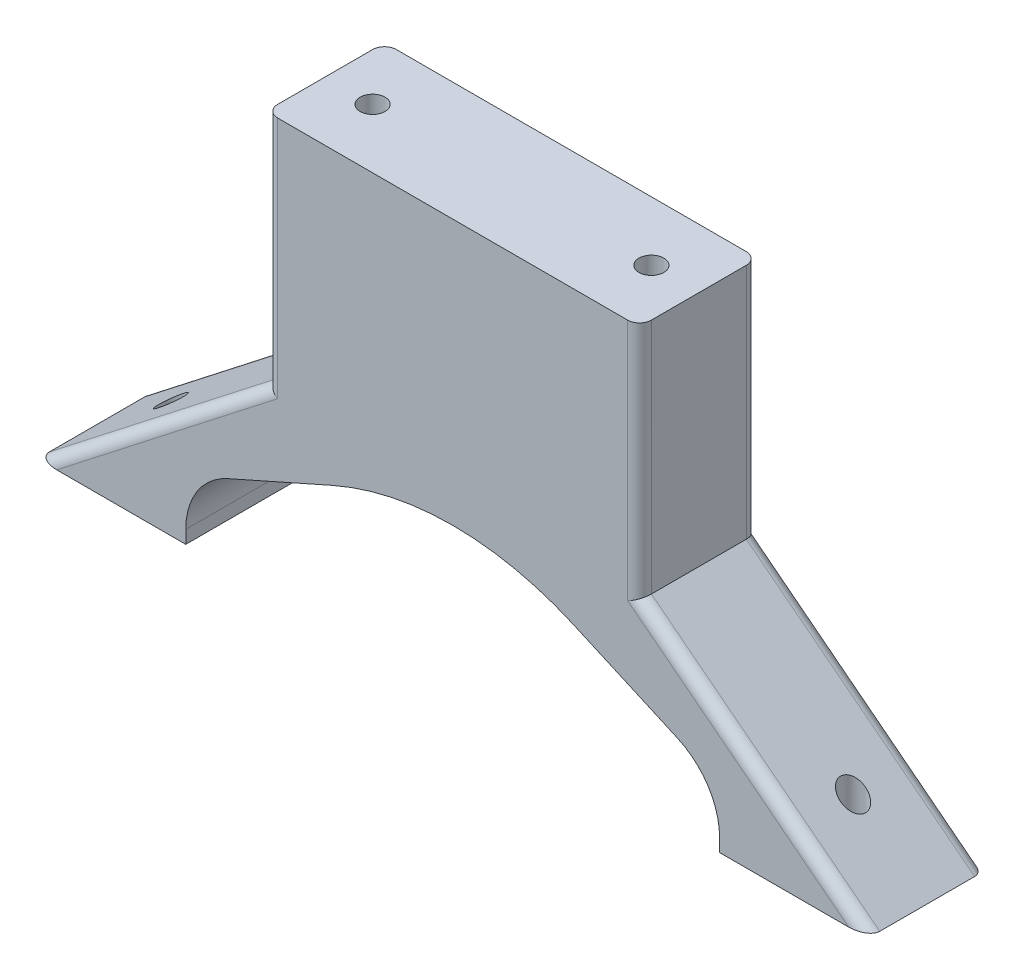
SolidWorks part; units mm, degrees
ref_plane "Front Plane" through (0, 0, 0) normal (0, 0, 1) x (1, 0, 0)
ref_plane "Top Plane" through (0, 0, 0) normal (0, 1, 0) x (1, 0, 0)
ref_plane "Right Plane" through (0, 0, 0) normal (1, 0, 0) x (0, 0, -1)
sketch "Sketch8" plane through (0, 0, 0) normal (0, 0, 1) x (1, 0, 0)
  line L0 (0, -43.5321) -> (-38.5, -73.5321)
  line L1 (0, -3.5321) -> (63, -3.5321)
  line L2 (0, -3.5321) -> (0, -43.5321)
  line L3 (0, -43.5321) -> (63, -43.5321)
  line L4 (63, -3.5321) -> (63, -43.5321)
  line L5 (31.5, -1023.6556) -> (31.5, 48976.3444) construction
  line L6 (-13.5, -63.5321) -> (11.2429, -52.5484)
  line L7 (-38.5, -73.5321) -> (-13.5, -73.5321)
  line L8 (76.5, -73.5321) -> (76.5, -63.5321)
  line L9 (-25.6667, -63.5321) -> (-13.5, -63.5321)
  line L10 (-13.5, -73.5321) -> (-13.5, -63.5321)
  line L11 (101.5, -73.5321) -> (76.5, -73.5321)
  line L12 (88.6667, -63.5321) -> (76.5, -63.5321)
  line L13 (63, -43.5321) -> (101.5, -73.5321)
  line L14 (76.5, -63.5321) -> (51.8568, -52.5664)
  arc A0 (51.8568, -52.5664) -> (11.2429, -52.5484) centre (31.5296, -98.248) ccw
  point P8 (31.5, -43.5321)
  point P17 (31.8245, -23.5321)
  point P19 (31.5539, -43.5321)
  dimension "D7" = 50
  dimension "D1" = 40
  dimension "D2" = 63
  dimension "D3" = 30
  dimension "D4" = 70
  dimension "D5" = 10
  dimension "D6" = 25
extrude "Boss-Extrude3" add sketch "Sketch8" against normal blind 20 separate body contours L3 L5 L1 L2 | L0 L9 L6 L3 | L7 L10 L9 L0 | L5 L3 L4 L1 | L13 L12 L8 L11 | L14 L12 L13 L3
hole_wizard "Tap Drill for M5x0.8 Tap2" positions "Sketch11" profile "Sketch12" hole size "M5x0.8" standard "ANSI Metric" end condition through all
sketch "Sketch11" plane through (0, -73.5321, 0) normal (0, -1, 0) x (-1, 0, 0)
  point P0 (26, 10)
  point P2 (-89, 10)
sketch "Sketch12" plane through (-26, -73.5321, -10) normal (1, 0, 0) x (0, 0, -1)
  line L0 (0, 0) -> (0, 70)
  line L1 (0, 70) -> (2.1, 70)
  line L2 (2.1, 70) -> (2.1, 0)
  line L5 (2.1, 0) -> (0, 0)
  line L11 (0, -6.35) -> (0, 107.95) construction
  dimension "Thru Hole Dia." = 4.2
  dimension "Thru Hole Depth" = 70
fillet "Fillet4" radius 2 8 edges at (82.25, -58.5321, 0) (82.25, -58.5321, -20) (-19.25, -58.5321, 0) (-19.25, -58.5321, -20) (63, -23.5321, 0) (63, -23.5321, -20) (0, -23.5321, 0) (0, -23.5321, -20)
hole_wizard "Tap Drill for M5x0.8 Tap3" positions "Sketch13" profile "Sketch14" hole size "M5x0.8" standard "ANSI Metric" end condition through all
sketch "Sketch13" plane through (0, -3.5321, 0) normal (0, 1, 0) x (1, 0, 0)
  line L0 (0, 18) -> (0, 2) construction
  point P0 (8, 10)
  point P2 (55, 10)
  dimension "D1" = 47
  dimension "D2" = 8
sketch "Sketch14" plane through (8, -3.5321, -10) normal (1, 0, 0) x (0, 0, 1)
  line L0 (0, 0) -> (0, 70)
  line L1 (0, 70) -> (2.1, 70)
  line L2 (2.1, 70) -> (2.1, 0)
  line L5 (2.1, 0) -> (0, 0)
  line L11 (0, -6.35) -> (0, 107.95) construction
  dimension "Thru Hole Dia." = 4.2
  dimension "Thru Hole Depth" = 70
fillet "Fillet6" radius 12 2 edges at (76.5, -63.5321, -10) (-13.5, -63.5321, -10)
